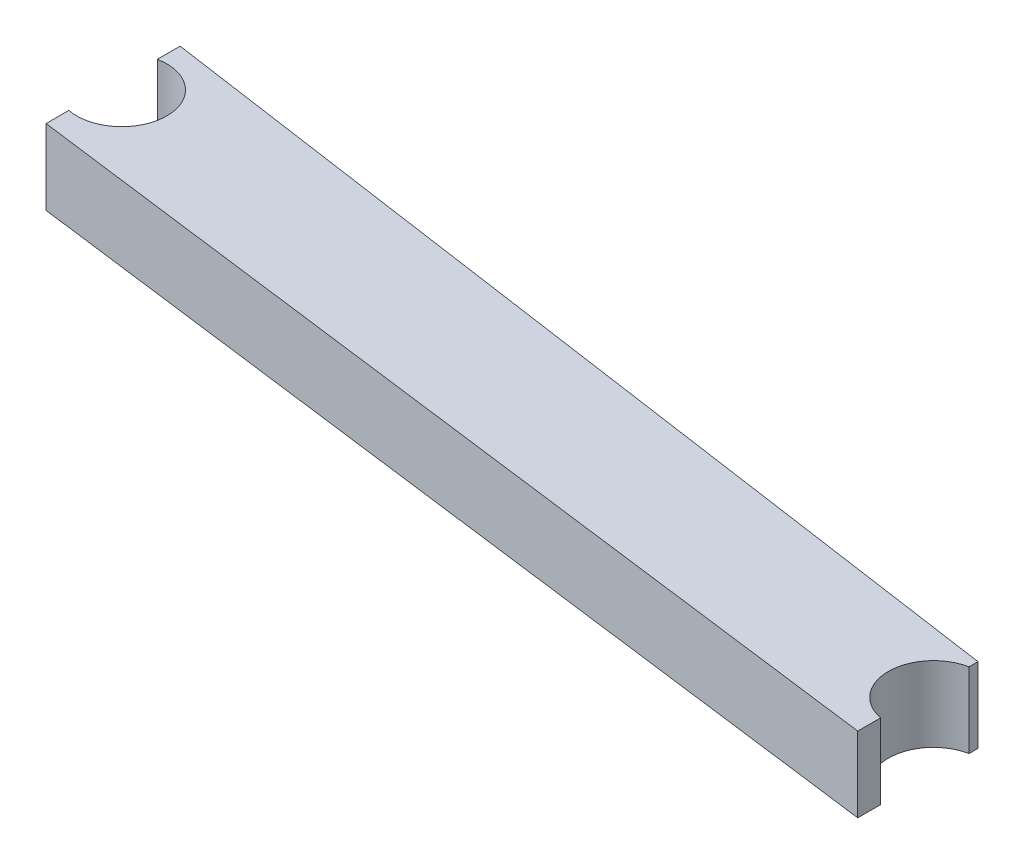
SolidWorks part; units mm, degrees
ref_plane "前视基准面" through (0, 0, 0) normal (0, 0, 1) x (1, 0, 0)
ref_plane "上视基准面" through (0, 0, 0) normal (0, 1, 0) x (1, 0, 0)
ref_plane "右视基准面" through (0, 0, 0) normal (1, 0, 0) x (0, 0, -1)
other "Configuration Table"
sketch "草图1" plane through (0, 0, 0) normal (0, 1, 0) x (1, 0, 0)
  line L0 (17.42, -58.46) -> (79.42, -66.46)
  line L1 (79.42, -66.46) -> (79.42, -58.46)
  line L2 (79.42, -58.46) -> (17.42, -49.54)
  line L3 (17.42, -49.54) -> (17.42, -58.46)
extrude "凸台-拉伸1" add sketch "草图1" along normal blind 5 from offset 5
sketch "草图2" plane through (0, 0, 0) normal (0, 1, 0) x (1, 0, 0)
  circle A0 centre (18, -54) radius 3
  circle A1 centre (80, -62) radius 3
extrude "切除-拉伸2" cut sketch "草图2" along normal through all
